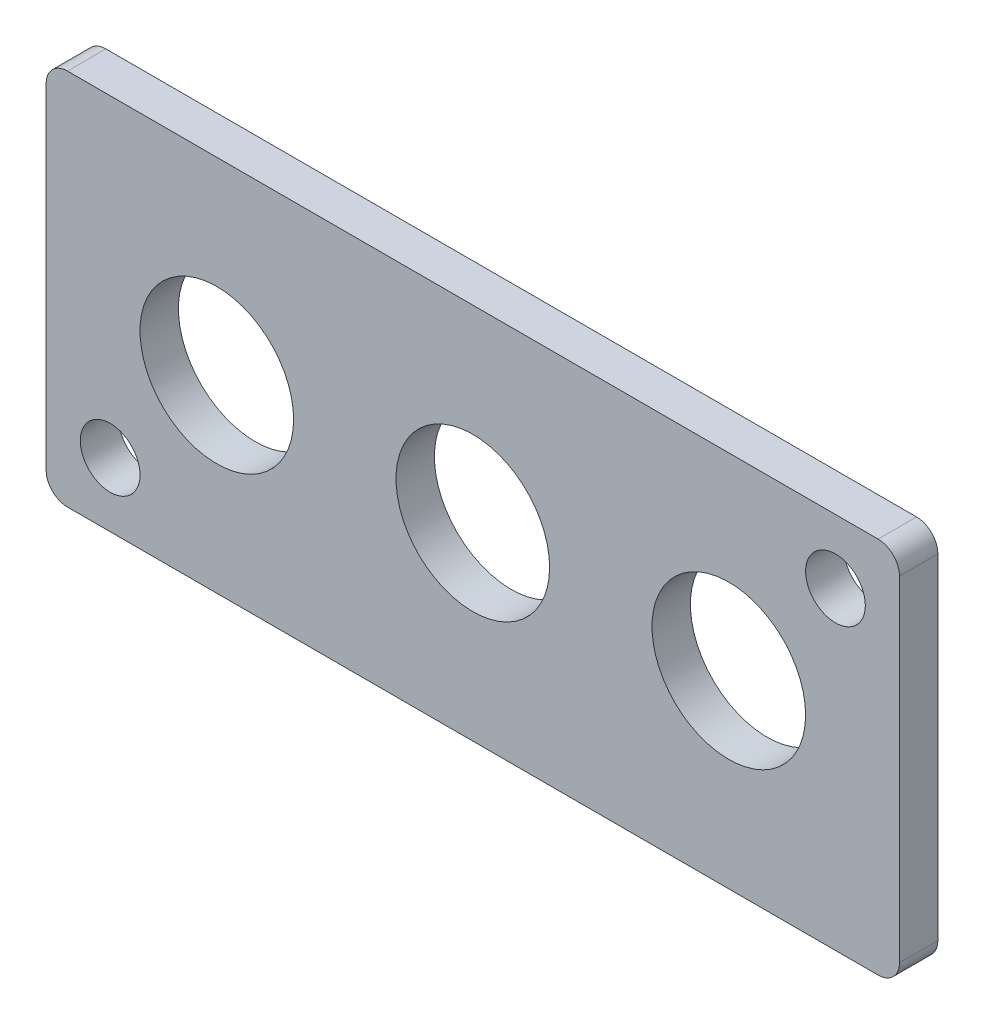
SolidWorks part; units mm, degrees
ref_plane "前视基准面" through (0, 0, 0) normal (0, 0, 1) x (1, 0, 0)
ref_plane "上视基准面" through (0, 0, 0) normal (0, 1, 0) x (1, 0, 0)
ref_plane "右视基准面" through (0, 0, 0) normal (1, 0, 0) x (0, 0, -1)
other "Configuration Table"
sketch "草图1" plane through (0, 0, 0) normal (0, 0, 1) x (1, 0, 0)
  line L0 (52, 45.5) -> (90, 45.5)
  line L1 (91, 46.5) -> (91, 62.2)
  line L2 (90, 63.2) -> (52, 63.2)
  line L3 (51, 62.2) -> (51, 46.5)
  arc A0 (90, 45.5) -> (91, 46.5) centre (90, 46.5) ccw
  arc A1 (91, 62.2) -> (90, 63.2) centre (90, 62.2) ccw
  arc A2 (52, 63.2) -> (51, 62.2) centre (52, 62.2) ccw
  arc A3 (51, 46.5) -> (52, 45.5) centre (52, 46.5) ccw
extrude "Retaining_plate" add sketch "草图1" along normal blind 1.8 from offset 33.8
sketch "草图2" plane through (0, 0, 0) normal (0, 0, 1) x (1, 0, 0)
  circle A0 centre (59, 54.355) radius 3.6
  circle A1 centre (71, 54.355) radius 3.6
  circle A2 centre (83, 54.355) radius 3.6
  circle A3 centre (54, 48.5) radius 1.4
  circle A4 centre (88, 60.2) radius 1.4
extrude "Plungers_and_M2p5_screws" cut sketch "草图2" against normal through all and the other way through all
